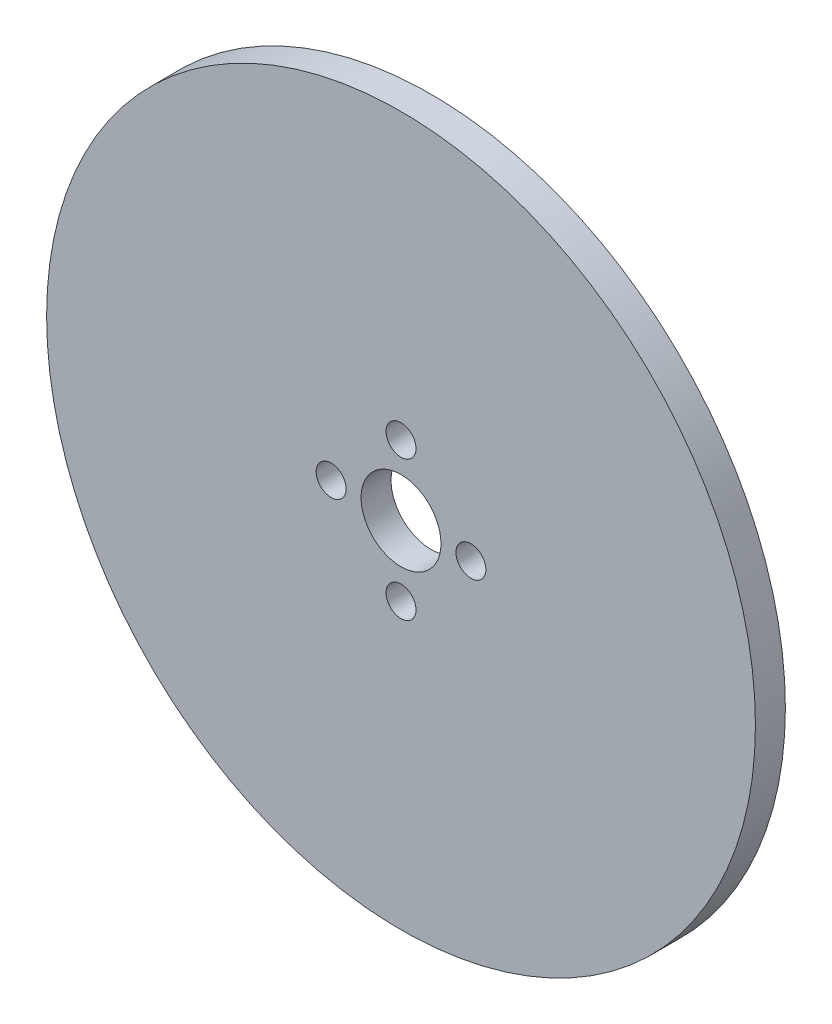
SolidWorks part; units mm, degrees
ref_plane "前视基准面" through (0, 0, 0) normal (0, 0, 1) x (1, 0, 0)
ref_plane "上视基准面" through (0, 0, 0) normal (0, 1, 0) x (1, 0, 0)
ref_plane "右视基准面" through (0, 0, 0) normal (1, 0, 0) x (0, 0, -1)
sketch "草图1" plane through (0, 0, 0) normal (0, 0, 1) x (1, 0, 0)
  circle A0 centre (0, 0) radius 35.5
  circle A1 centre (0, 0) radius 4
  circle A2 centre (7, 0) radius 1.5
  circle A3 centre (0, -7) radius 1.5
  circle A4 centre (-7, 0) radius 1.5
  circle A5 centre (0, 7) radius 1.5
  point P15 (0, 0)
  dimension "D1" = 4
extrude "凸台-拉伸2" add sketch "草图1" along normal blind 3
